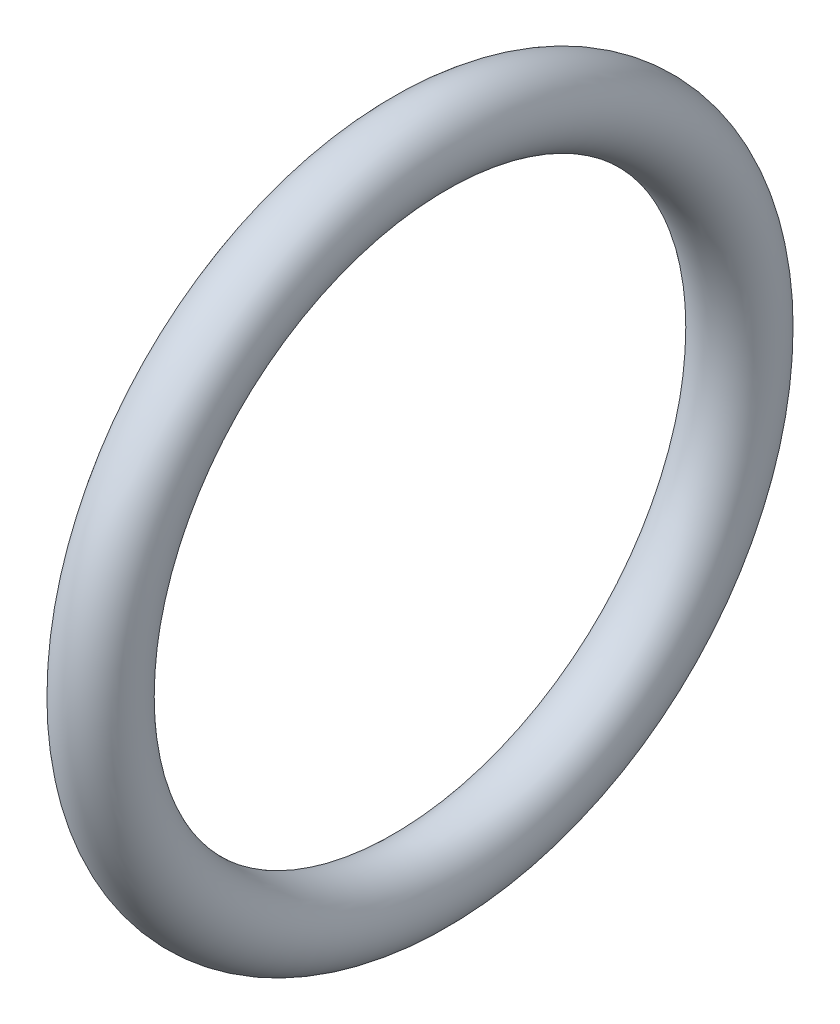
SolidWorks part; units mm, degrees
material "天然橡胶"
ref_plane "前视基准面" through (0, 0, 0) normal (0, 0, 1) x (1, 0, 0)
ref_plane "上视基准面" through (0, 0, 0) normal (0, 1, 0) x (1, 0, 0)
ref_plane "右视基准面" through (0, 0, 0) normal (1, 0, 0) x (0, 0, -1)
sketch "草图1" plane through (0, 0, 0) normal (0, 0, 1) x (1, 0, 0)
  line L0 (0, 0) -> (54.1489, 0) construction
  circle A0 centre (0, 10.1) radius 1.2
  dimension "D1" = 11.3
  dimension "D2" = 8.9
revolve "旋转1" add sketch "草图1" angle 360 about L0
ref_plane "基准面1" through (0, 0, 0) normal (1, 0, 0) x (0, 0, -1)
